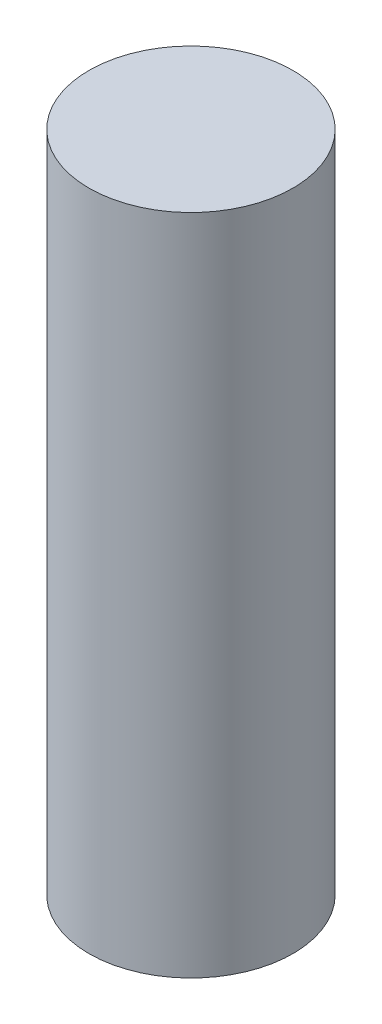
SolidWorks part; units mm, degrees
material "PE High Density"
ref_plane "Front Plane" through (0, 0, 0) normal (0, 0, 1) x (1, 0, 0)
ref_plane "Top Plane" through (0, 0, 0) normal (0, 1, 0) x (1, 0, 0)
ref_plane "Right Plane" through (0, 0, 0) normal (1, 0, 0) x (0, 0, -1)
sketch "Sketch1" plane through (0, 0, 0) normal (0, 1, 0) x (1, 0, 0)
  circle A0 centre (0, 0) radius 50
  dimension "D1" = 100
extrude "Boss-Extrude1" add sketch "Sketch1" along normal blind 325
scale "Scale1" scale about centroid uniform scaling yes scale factor 0.75
